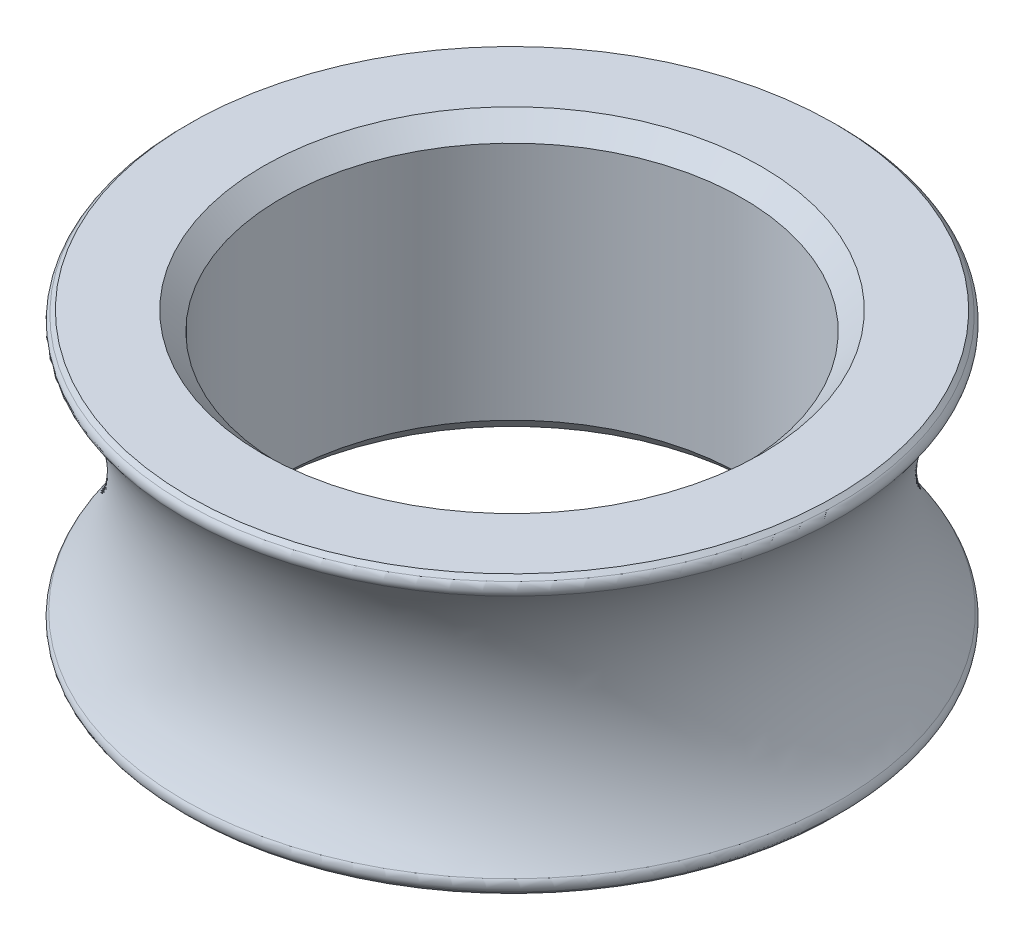
SolidWorks part; units mm, degrees
ref_plane "Front Plane" through (0, 0, 0) normal (0, 0, 1) x (1, 0, 0)
ref_plane "Top Plane" through (0, 0, 0) normal (0, 1, 0) x (1, 0, 0)
ref_plane "Right Plane" through (0, 0, 0) normal (1, 0, 0) x (0, 0, -1)
sketch "Sketch1" plane through (0, 0, 0) normal (0, 1, 0) x (1, 0, 0)
  circle A0 centre (0, 0) radius 2.5 construction
  circle A1 centre (0, 0) radius 2.5
  circle A2 centre (0, 0) radius 3.7
  dimension "D1" = 5
  dimension "D3" = 1.2
extrude "Boss-Extrude1" add sketch "Sketch1" along normal mid plane 3
sketch "Sketch2" plane through (0, 0, 0) normal (1, 0, 0) x (0, 0, -1)
  line L0 (-3.7, -1.5) -> (-3.7, 1.5)
  line L1 (-3.7, 1.5) -> (-3.7, -1.5) construction
  line L2 (-2.5, 1.5) -> (-2.5, -1.5) construction
  arc A0 (-3.7, 1.5) -> (-3.7, -1.5) centre (-5.275, 0) cw
  point P11 (-3.1, 0)
  dimension "D1" = 0.6
sweep "Cut-Sweep1" cut profiles "Sketch2" path edge at (0, 1.5, 3.7)
chamfer "Chamfer1" distance 0.2 angle 45 3 edges at (0, -1.5, 2.5) (0, 1.5, 2.5) (0, -1.5, 3.7)
chamfer "Chamfer2" distance 0.2 angle 45 1 edges at (0, 1.5, 3.7)
fillet "Fillet1" radius 0.1 2 edges at (0, 1.3943, -3.6057) (0, -1.3943, 3.6057)
